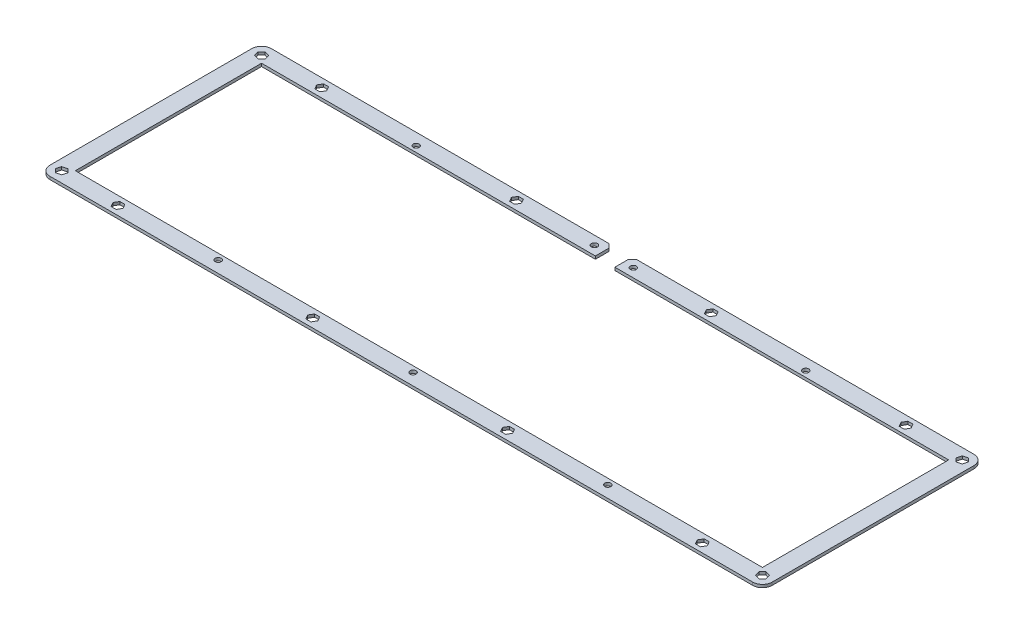
SolidWorks part; units mm, degrees
ref_plane "Front Plane" through (0, 0, 0) normal (0, 0, 1) x (1, 0, 0)
ref_plane "Top Plane" through (0, 0, 0) normal (0, 1, 0) x (1, 0, 0)
ref_plane "Right Plane" through (0, 0, 0) normal (1, 0, 0) x (0, 0, -1)
sketch "Sketch1" plane through (0, 0, 0) normal (0, 1, 0) x (1, 0, 0)
  line L0 (0, 108.6) -> (0, 5)
  line L1 (9, 104.6) -> (9, 9)
  line L2 (365.775, 0) -> (5, 0)
  line L3 (361.775, 9) -> (9, 9)
  line L4 (370.775, 108.6) -> (370.775, 5)
  line L5 (361.775, 104.6) -> (361.775, 9)
  line L6 (180.3875, 104.6) -> (180.3875, 111.6)
  line L7 (180.3875, 111.6) -> (178.3875, 113.6)
  line L8 (190.3875, 111.6) -> (192.3875, 113.6)
  line L9 (190.3875, 104.6) -> (190.3875, 111.6)
  line L10 (9, 104.6) -> (180.3875, 104.6)
  line L11 (5, 113.6) -> (178.3875, 113.6)
  line L12 (190.3875, 104.6) -> (361.775, 104.6)
  line L13 (192.3875, 113.6) -> (365.775, 113.6)
  line L14 (234.0885, 111.35) -> (236.6865, 111.35)
  line L15 (236.6865, 111.35) -> (237.9856, 109.1)
  line L16 (237.9856, 109.1) -> (236.6865, 106.85)
  line L17 (236.6865, 106.85) -> (234.0885, 106.85)
  line L18 (234.0885, 106.85) -> (232.7894, 109.1)
  line L19 (232.7894, 109.1) -> (234.0885, 111.35)
  line L20 (334.0885, 111.35) -> (336.6865, 111.35)
  line L21 (336.6865, 111.35) -> (337.9856, 109.1)
  line L22 (337.9856, 109.1) -> (336.6865, 106.85)
  line L23 (336.6865, 106.85) -> (334.0885, 106.85)
  line L24 (334.0885, 106.85) -> (332.7894, 109.1)
  line L25 (332.7894, 109.1) -> (334.0885, 111.35)
  line L26 (365.9474, 110.6095) -> (367.7846, 108.7724)
  line L27 (367.7846, 108.7724) -> (367.1121, 106.2629)
  line L28 (367.1121, 106.2629) -> (364.6026, 105.5905)
  line L29 (364.6026, 105.5905) -> (362.7655, 107.4276)
  line L30 (362.7655, 107.4276) -> (363.4379, 109.9371)
  line L31 (363.4379, 109.9371) -> (365.9474, 110.6095)
  line L32 (136.6865, 111.35) -> (134.0885, 111.35)
  line L33 (134.0885, 111.35) -> (132.7894, 109.1)
  line L34 (132.7894, 109.1) -> (134.0885, 106.85)
  line L35 (134.0885, 106.85) -> (136.6865, 106.85)
  line L36 (136.6865, 106.85) -> (137.9856, 109.1)
  line L37 (137.9856, 109.1) -> (136.6865, 111.35)
  line L38 (36.6865, 111.35) -> (34.0885, 111.35)
  line L39 (34.0885, 111.35) -> (32.7894, 109.1)
  line L40 (32.7894, 109.1) -> (34.0885, 106.85)
  line L41 (34.0885, 106.85) -> (36.6865, 106.85)
  line L42 (36.6865, 106.85) -> (37.9856, 109.1)
  line L43 (37.9856, 109.1) -> (36.6865, 111.35)
  line L44 (4.8276, 110.6095) -> (2.9905, 108.7724)
  line L45 (2.9905, 108.7724) -> (3.6629, 106.2629)
  line L46 (3.6629, 106.2629) -> (6.1724, 105.5905)
  line L47 (6.1724, 105.5905) -> (8.0096, 107.4276)
  line L48 (8.0096, 107.4276) -> (7.3371, 109.9371)
  line L49 (7.3371, 109.9371) -> (4.8276, 110.6095)
  line L50 (234.0885, 2.25) -> (236.6865, 2.25)
  line L51 (236.6865, 2.25) -> (237.9856, 4.5)
  line L52 (237.9856, 4.5) -> (236.6865, 6.75)
  line L53 (236.6865, 6.75) -> (234.0885, 6.75)
  line L54 (234.0885, 6.75) -> (232.7894, 4.5)
  line L55 (232.7894, 4.5) -> (234.0885, 2.25)
  line L56 (334.0885, 2.25) -> (336.6865, 2.25)
  line L57 (336.6865, 2.25) -> (337.9856, 4.5)
  line L58 (337.9856, 4.5) -> (336.6865, 6.75)
  line L59 (336.6865, 6.75) -> (334.0885, 6.75)
  line L60 (334.0885, 6.75) -> (332.7894, 4.5)
  line L61 (332.7894, 4.5) -> (334.0885, 2.25)
  line L62 (365.9474, 2.9905) -> (367.7846, 4.8276)
  line L63 (367.7846, 4.8276) -> (367.1121, 7.3371)
  line L64 (367.1121, 7.3371) -> (364.6026, 8.0095)
  line L65 (364.6026, 8.0095) -> (362.7655, 6.1724)
  line L66 (362.7655, 6.1724) -> (363.4379, 3.6629)
  line L67 (363.4379, 3.6629) -> (365.9474, 2.9905)
  line L68 (136.6865, 2.25) -> (134.0885, 2.25)
  line L69 (134.0885, 2.25) -> (132.7894, 4.5)
  line L70 (132.7894, 4.5) -> (134.0885, 6.75)
  line L71 (134.0885, 6.75) -> (136.6865, 6.75)
  line L72 (136.6865, 6.75) -> (137.9856, 4.5)
  line L73 (137.9856, 4.5) -> (136.6865, 2.25)
  line L74 (36.6865, 2.25) -> (34.0885, 2.25)
  line L75 (34.0885, 2.25) -> (32.7894, 4.5)
  line L76 (32.7894, 4.5) -> (34.0885, 6.75)
  line L77 (34.0885, 6.75) -> (36.6865, 6.75)
  line L78 (36.6865, 6.75) -> (37.9856, 4.5)
  line L79 (37.9856, 4.5) -> (36.6865, 2.25)
  line L80 (4.8276, 2.9905) -> (2.9905, 4.8276)
  line L81 (2.9905, 4.8276) -> (3.6629, 7.3371)
  line L82 (3.6629, 7.3371) -> (6.1724, 8.0095)
  line L83 (6.1724, 8.0095) -> (8.0096, 6.1724)
  line L84 (8.0096, 6.1724) -> (7.3371, 3.6629)
  line L85 (7.3371, 3.6629) -> (4.8276, 2.9905)
  arc A0 (365.775, 0) -> (370.775, 5) centre (365.775, 5) ccw
  arc A1 (370.775, 108.6) -> (365.775, 113.6) centre (365.775, 108.6) ccw
  arc A2 (0, 5) -> (5, 0) centre (5, 5) ccw
  arc A3 (5, 113.6) -> (0, 108.6) centre (5, 108.6) ccw
  circle A4 centre (195.3875, 109.1) radius 1.55
  circle A5 centre (175.3875, 109.1) radius 1.55
  circle A6 centre (85.3875, 107.6) radius 1.55
  circle A7 centre (285.3875, 107.6) radius 1.55
  circle A8 centre (85.3875, 6) radius 1.55
  circle A9 centre (185.3875, 6) radius 1.55
  circle A10 centre (285.3875, 6) radius 1.55
extrude "Boss-Extrude1" add sketch "Sketch1" against normal blind 1.5
